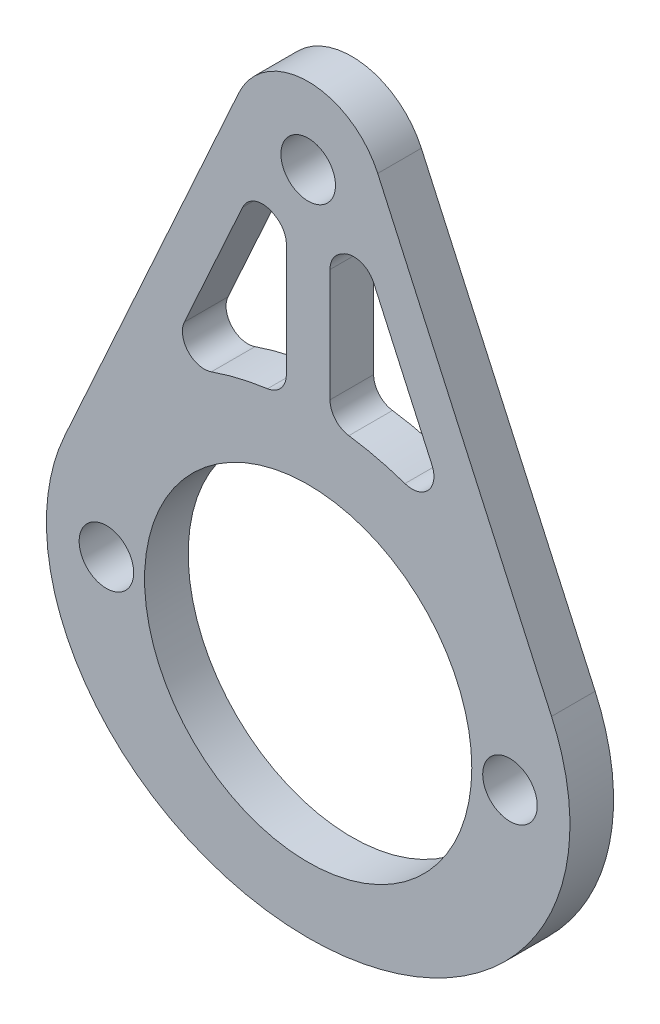
SolidWorks part; units mm, degrees
material "A2017"
ref_plane "正面" through (0, 0, 0) normal (0, 0, 1) x (1, 0, 0)
ref_plane "平面" through (0, 0, 0) normal (0, 1, 0) x (1, 0, 0)
ref_plane "右側面" through (0, 0, 0) normal (1, 0, 0) x (0, 0, -1)
sketch "ｽｹｯﾁ1" plane through (0, 0, 0) normal (0, 0, 1) x (1, 0, 0)
  line L0 (0, 0) -> (9.25, 0) construction
  line L1 (0, 0) -> (0, 7.5) construction
  line L2 (0, 0) -> (0, 20) construction
  line L3 (-11.1545, 3.8716) -> (-3.1877, 21.4451)
  line L4 (11.1545, 3.8716) -> (3.1877, 21.4451)
  circle A0 centre (0, 0) radius 7.5
  circle A1 centre (9.25, 0) radius 2.75 construction
  circle A2 centre (9.25, 0) radius 1
  circle A3 centre (0, 0) radius 10.5 construction
  circle A4 centre (-9.25, 0) radius 1
  circle A5 centre (0, 20) radius 3 construction
  arc A6 (3.1877, 21.4451) -> (-3.1877, 21.4451) centre (0, 20) ccw
  ellipse E0 centre (0, 0) end of major axis (12, 0) minor radius 10.5 (-11.1545, 3.8716) -> (11.1545, 3.8716) ccw
  dimension "D1" = 18.5
  dimension "D2" = 15
  dimension "D3" = 5.5
  dimension "D4" = 2
  dimension "D7" = 6
  dimension "D8" = 0.5
  dimension "D6" = 20
  dimension "D5" = 3
extrude "ﾎﾞｽ - 押し出し1" add sketch "ｽｹｯﾁ1" along normal blind 2
hole_wizard "M3 ねじ穴1" positions "ｽｹｯﾁ2" profile "ｽｹｯﾁ3" tap size "M3" standard "JIS" end condition through all
sketch "ｽｹｯﾁ2" plane through (0, 0, 0) normal (0, 0, -1) x (-1, 0, 0)
  point P0 (-9.25, 0)
  point P3 (9.25, 0)
sketch "ｽｹｯﾁ3" plane through (9.25, 0, 0) normal (1, 0, 0) x (0, 1, 0)
  line L0 (0, 0) -> (0, 2)
  line L1 (0, 2) -> (1.25, 2)
  line L2 (1.25, 2) -> (1.25, 0)
  line L5 (1.25, 0) -> (0, 0)
  line L11 (0, -6.35) -> (0, 107.95) construction
  dimension "次ｻｰﾌｪｽまでのねじ下穴ﾄﾞﾘﾙ直径" = 2.5
  dimension "次ｻｰﾌｪｽまでのねじ下穴ﾄﾞﾘﾙの深さ" = 2
cosmetic thread "穴のねじ山1" parameters "D2"=3
cosmetic thread "穴のねじ山2" parameters "D2"=3
sketch "ｽｹｯﾁ4" plane through (0, 0, 0) normal (0, 0, -1) x (-1, 0, 0)
  line L0 (0, 20) -> (0, 0) construction
  line L2 (1, 10.4635) -> (-1, 10.4635)
  line L3 (1, 10.4635) -> (1, 17.1716)
  line L4 (1, 17.1716) -> (-1, 17.1716)
  line L5 (-1, 10.4635) -> (-1, 17.1716)
  line L6 (1, 10.4635) -> (-1, 17.1716) construction
  line L7 (1, 17.1716) -> (-1, 10.4635) construction
  line L9 (1.3662, 20.6193) -> (9.3329, 3.0458)
  line L10 (1.3662, 20.6193) -> (9.3329, 3.0458)
  line L12 (-9.3329, 3.0458) -> (-1.3662, 20.6193)
  line L13 (-9.3329, 3.0458) -> (-1.3662, 20.6193)
  circle A2 centre (0, 20) radius 3
  ellipse E0 centre (0, 0) end of major axis (-12, 0) minor radius 10.5 (8.5484, -7.369) -> (-8.5484, -7.369) ccw construction
  ellipse E1 centre (0, 0) end of major axis (-12, 0) minor radius 10.5 (8.5484, -7.369) -> (-8.5484, -7.369) ccw
  point P18 (0, 13.8175)
  dimension "D4" = 6
  dimension "D1" = 2
  dimension "D2" = 2
  dimension "D3" = 2
extrude "ｶｯﾄ - 押し出し1" cut sketch "ｽｹｯﾁ4" against normal through all contours E1 L5 A2 L13 | E1 L10 A2 L3
fillet "ﾌｨﾚｯﾄ1" radius 1 8 edges at (-1, 17.1716, 1) (-2.4389, 18.2531, 1) (-6.7885, 8.6583, 1) (2.4389, 18.2531, 1) (1, 17.1716, 1) (1, 10.4635, 1) (6.7885, 8.6583, 1) (-1, 10.4635, 1)
hole_wizard "M3 ねじ穴2" positions "ｽｹｯﾁ5" profile "ｽｹｯﾁ6" tap size "M3" standard "JIS" end condition through all
sketch "ｽｹｯﾁ5" plane through (0, 0, 2) normal (0, 0, 1) x (1, 0, 0)
  point P0 (0, 20)
sketch "ｽｹｯﾁ6" plane through (0, 20, 2) normal (1, 0, 0) x (0, -1, 0)
  line L0 (0, 0) -> (0, 2)
  line L1 (0, 2) -> (1.25, 2)
  line L2 (1.25, 2) -> (1.25, 0)
  line L5 (1.25, 0) -> (0, 0)
  line L11 (0, -6.35) -> (0, 107.95) construction
  dimension "次ｻｰﾌｪｽまでのねじ下穴ﾄﾞﾘﾙ直径" = 2.5
  dimension "次ｻｰﾌｪｽまでのねじ下穴ﾄﾞﾘﾙの深さ" = 2
cosmetic thread "穴のねじ山3" parameters "D2"=3
